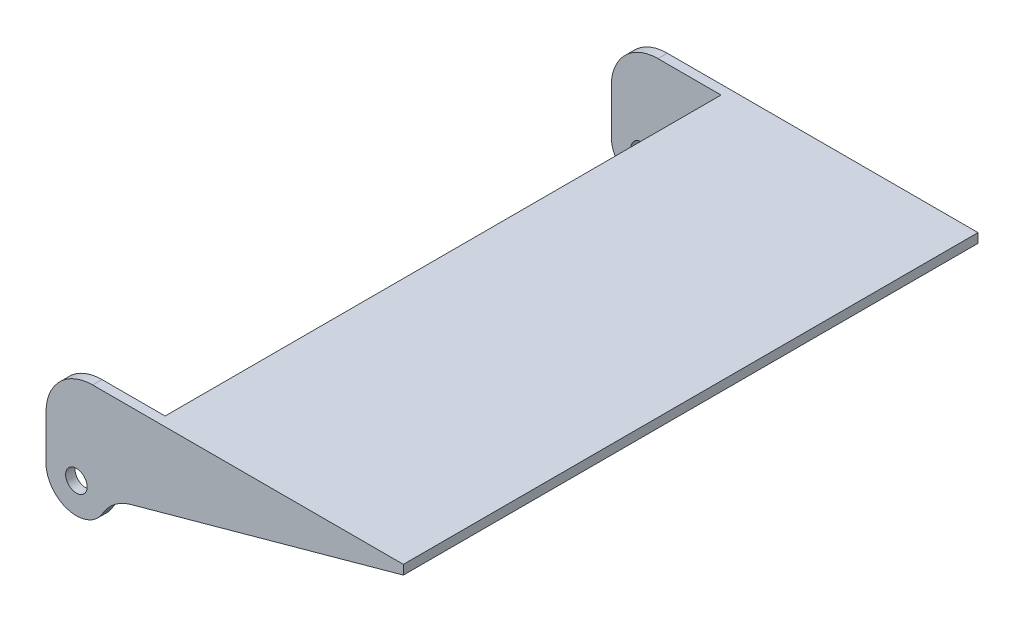
SolidWorks part; units mm, degrees
ref_plane "Front Plane" through (0, 0, 0) normal (0, 0, 1) x (1, 0, 0)
ref_plane "Top Plane" through (0, 0, 0) normal (0, 1, 0) x (1, 0, 0)
ref_plane "Right Plane" through (0, 0, 0) normal (1, 0, 0) x (0, 0, -1)
sketch "Sketch1" plane through (0, 0, 0) normal (0, 1, 0) x (1, 0, 0)
  line L1 (-25, -61.5) -> (25, -61.5)
  line L2 (-25, -61.5) -> (-25, 61.5)
  line L3 (-25, 61.5) -> (25, 61.5)
  line L4 (25, -61.5) -> (25, 61.5)
  line L5 (-25, -61.5) -> (25, 61.5) construction
  line L6 (-25, 61.5) -> (25, -61.5) construction
  point P0 (0, 0)
  dimension "D1" = 50
  dimension "D2" = 123
extrude "Boss-Extrude1" add sketch "Sketch1" along normal blind 2
sketch "Sketch2" plane through (0, 0, 61.5) normal (0, 0, 1) x (1, 0, 0)
  line L1 (-41.5005, 2) -> (25, 2)
  line L2 (-51.5005, -8) -> (-51.5005, -17.5)
  line L6 (25, 0) -> (25, 2)
  line L7 (25, 0) -> (-33.3505, -16.081)
  line L8 (-25, 2) -> (25, 2) construction
  arc A0 (-51.5005, -17.5) -> (-39.3639, -20.7389) centre (-45, -17.5) ccw
  arc A1 (-41.5005, 2) -> (-51.5005, -8) centre (-41.5005, -8) ccw
  arc A2 (-39.3639, -20.7389) -> (-33.3505, -16.081) centre (-30.6936, -25.7216) cw
  point P5 (30, 0)
  point P6 (0, 0)
  point P7 (-51.9641, -19.5718)
  point P9 (30, 2)
  point P17 (-38.4995, -17.5)
  point P18 (0, 0)
  point P19 (-34.8982, -24.9807)
  point P20 (-51.7902, -16.3847)
  point P21 (-45, -17.5)
  point P23 (-52.3697, -17.5)
  point P24 (0, 0)
  point P25 (0, 0)
  point P26 (-51.5005, -13)
  point P27 (0, 0)
  dimension "D1" = 10
  dimension "D2" = 10
extrude "Boss-Extrude2" add sketch "Sketch2" against normal up to surface (123 mm away) up to face at (0, 1, -61.5)
sketch "Sketch3" plane through (0, 0, 0) normal (1, 0, 0) x (0, 0, -1)
  line L0 (-61.5, 0) -> (61.5, 0) construction
  line L1 (-59.5, 0) -> (59.5, 0)
  line L2 (-59.5, 0) -> (-59.5, -24.0005)
  line L3 (-59.5, -24.0005) -> (59.5, -24.0005)
  line L4 (59.5, 0) -> (59.5, -24.0005)
  line L5 (-61.5, -24.0005) -> (61.5, -24.0005) construction
  line L6 (-61.5, -16.081) -> (-61.5, 0) construction
  line L7 (61.5, 0) -> (61.5, -16.081) construction
  dimension "D1" = 2
  dimension "D2" = 2
extrude "Cut-Extrude1" cut sketch "Sketch3" against normal through all both and the other way through all
sketch "Sketch4" plane through (0, 2, 0) normal (0, 1, 0) x (1, 0, 0)
  line L1 (-28, 59.5) -> (-58.227, 59.5)
  line L2 (-28, 59.5) -> (-28, -59.5)
  line L3 (-28, -59.5) -> (-58.227, -59.5)
  line L4 (-58.227, 59.5) -> (-58.227, -59.5)
  line L6 (-41.5005, -61.5) -> (25, -61.5) construction
  line L7 (25, -61.5) -> (25, 61.5) construction
  line L8 (25, 61.5) -> (-41.5005, 61.5) construction
  point P11 (0, 0)
  dimension "D1" = 2
  dimension "D2" = 53
  dimension "D3" = 2
extrude "Cut-Extrude2" cut sketch "Sketch4" against normal through all both and the other way through all
sketch "Sketch5" plane through (0, 0, 61.5) normal (0, 0, 1) x (1, 0, 0)
  circle A0 centre (-45, -17.5) radius 2.3
  dimension "D1" = 4.6
extrude "Cut-Extrude3" cut sketch "Sketch5" against normal through all both and the other way through all
